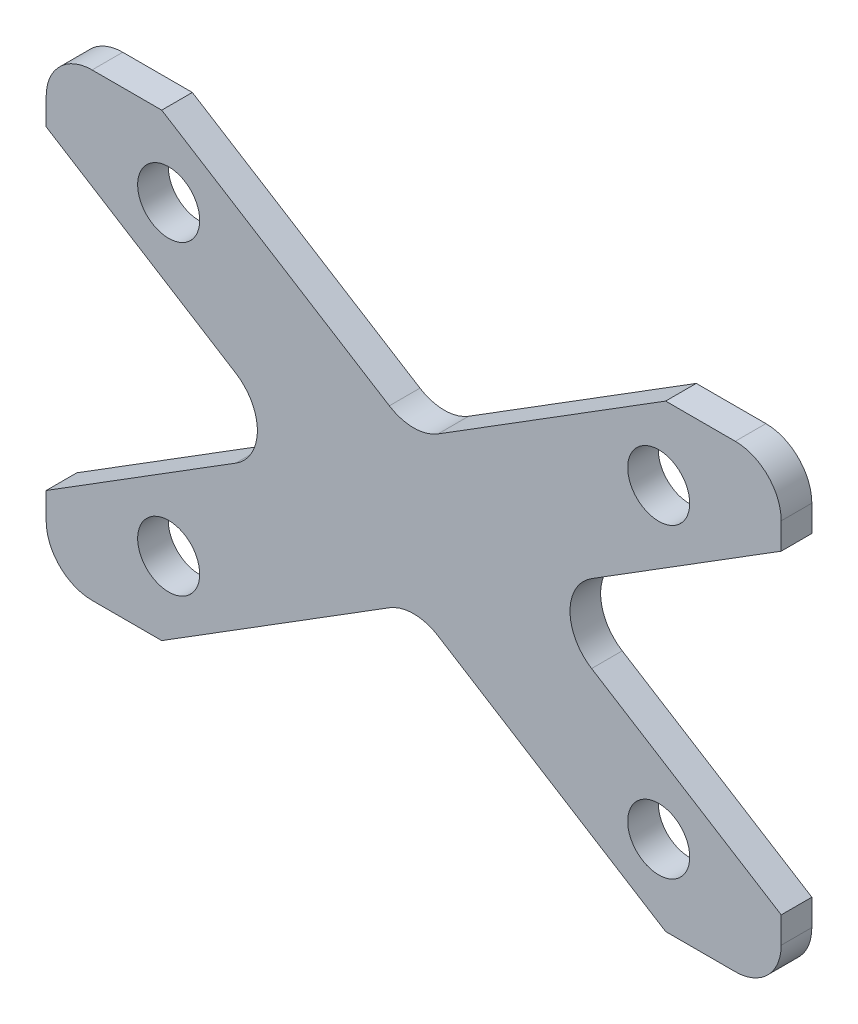
SolidWorks part; units mm, degrees
material "AISI 304"
ref_plane "Front Plane" through (0, 0, 0) normal (0, 0, 1) x (1, 0, 0)
ref_plane "Top Plane" through (0, 0, 0) normal (0, 1, 0) x (1, 0, 0)
ref_plane "Right Plane" through (0, 0, 0) normal (1, 0, 0) x (0, 0, -1)
sketch "Sketch1" plane through (0, 0, 0) normal (0, 0, 1) x (1, 0, 0)
  line L0 (-27.1795, 0) -> (24.0385, 0) construction
  line L1 (-24, 15) -> (-16.4528, 15)
  line L2 (-24, 15) -> (-24, 10.283)
  line L3 (-24, -15) -> (-16.4528, -15)
  line L4 (24, 15) -> (24, 10.283)
  line L5 (-24, 15) -> (24, -15) construction
  line L6 (-24, -15) -> (24, 15) construction
  line L7 (0, 26.6987) -> (0, -22.2115) construction
  line L8 (-24, 10) -> (24.0385, 10) construction
  line L9 (-16, 26.6987) -> (-16, -22.2115) construction
  line L10 (-24, 10.283) -> (-7.5472, 0)
  line L11 (-16.4528, -15) -> (0, -4.717)
  line L12 (-16.4528, 15) -> (0, 4.717)
  line L13 (-24, -10.283) -> (-7.5472, 0)
  line L14 (16.4528, 15) -> (24, 15)
  line L15 (-21.88, 18.392) -> (26.12, -11.608) construction
  line L16 (-26.12, 11.608) -> (21.88, -18.392) construction
  line L17 (-27.1795, 10) -> (24.0385, 10) construction
  line L18 (-26.12, -11.608) -> (21.88, 18.392) construction
  line L19 (-21.88, -18.392) -> (26.12, 11.608) construction
  line L20 (0, 4.717) -> (16.4528, 15)
  line L21 (7.5472, 0) -> (24, -10.283)
  line L22 (7.5472, 0) -> (24, 10.283)
  line L23 (0, -4.717) -> (16.4528, -15)
  line L24 (16.4528, -15) -> (24, -15)
  line L25 (-24, -10.283) -> (-24, -15)
  line L26 (24, -10.283) -> (24, -15)
  circle A0 centre (-16, 10) radius 2.025
  circle A1 centre (16, 10) radius 2.025
  circle A2 centre (16, -10) radius 2.025
  circle A3 centre (-16, -10) radius 2.025
  point P0 (0, 0)
  point P16 (-16, -10)
  point P17 (15.7051, -9.8157)
  point P48 (-52.5497, 21.7861)
  dimension "D5" = 4.05
  dimension "D1" = 48
  dimension "D2" = 30
  dimension "D3" = 10
  dimension "D4" = 16
  dimension "D9" = 4
  dimension "D6" = 2
  dimension "D7" = 2
extrude "Boss-Extrude1" add sketch "Sketch1" along normal blind 2
fillet "Fillet1" radius 3 8 edges at (0, 4.717, 1) (7.5472, 0, 1) (0, -4.717, 1) (-7.5472, 0, 1) (-24, -15, 1) (24, -15, 1) (24, 15, 1) (-24, 15, 1)
